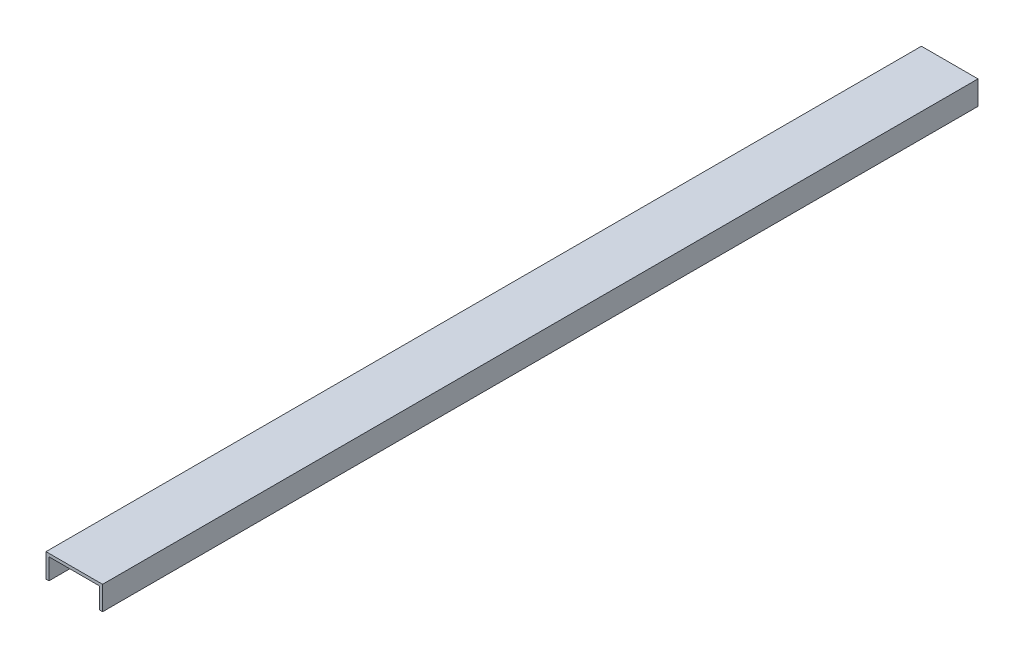
SolidWorks part; units mm, degrees
ref_plane "Front Plane" through (0, 0, 0) normal (0, 0, 1) x (1, 0, 0)
ref_plane "Top Plane" through (0, 0, 0) normal (0, 1, 0) x (1, 0, 0)
ref_plane "Right Plane" through (0, 0, 0) normal (1, 0, 0) x (0, 0, -1)
sketch "Sketch1" plane through (0, 0, 0) normal (0, 0, 1) x (1, 0, 0)
  line L0 (0, 0) -> (-8.5, 0)
  line L1 (-8.5, 0) -> (-8.5, -7)
  line L2 (-8.5, -7) -> (-9.5, -7)
  line L3 (-9.5, -7) -> (-9.5, 1)
  line L4 (-9.5, 1) -> (9.5, 1)
  line L5 (9.5, 1) -> (9.5, -7)
  line L6 (9.5, -7) -> (8.5, -7)
  line L7 (8.5, -7) -> (8.5, 0)
  line L8 (8.5, 0) -> (0, 0)
extrude "Boss-Extrude1" add sketch "Sketch1" along normal blind 294
